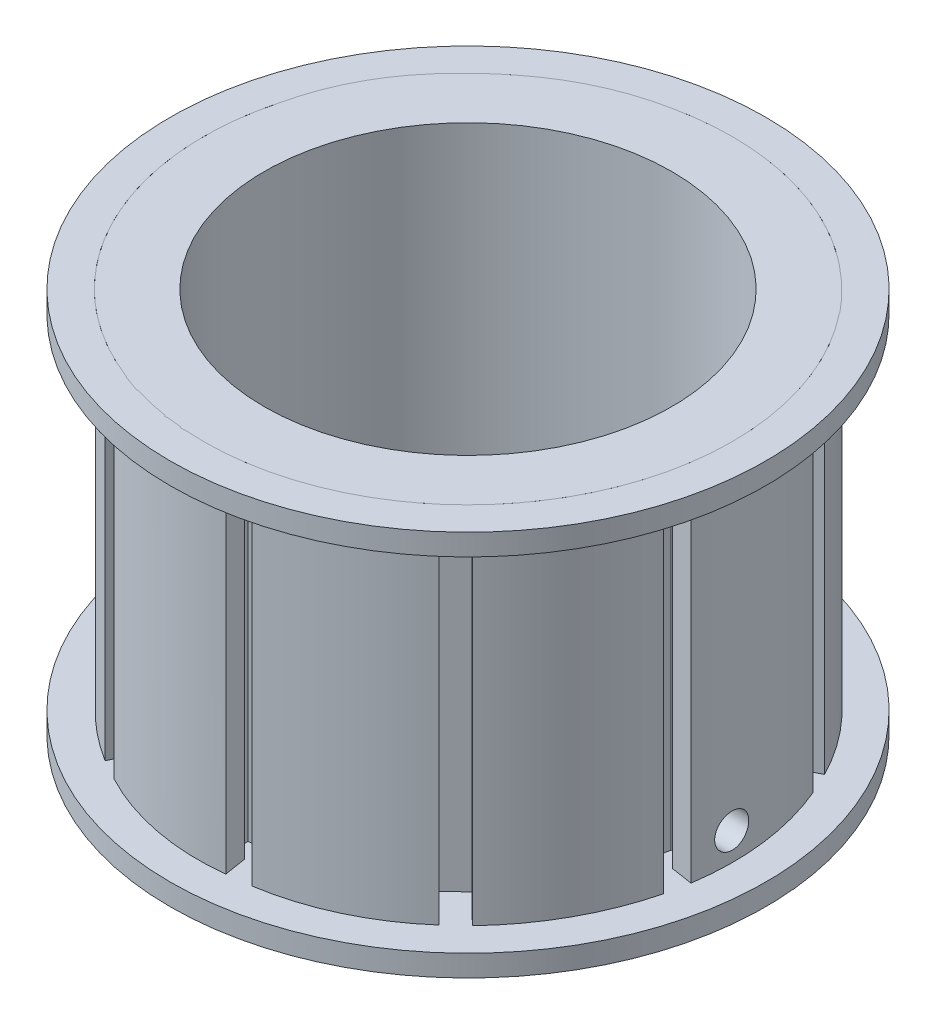
SolidWorks part; units mm, degrees
ref_plane "Alzado" through (0, 0, 0) normal (0, 0, 1) x (1, 0, 0)
ref_plane "Planta" through (0, 0, 0) normal (0, 1, 0) x (1, 0, 0)
ref_plane "Vista lateral" through (0, 0, 0) normal (1, 0, 0) x (0, 0, -1)
sketch "Sketch3" plane through (0, 0, 0) normal (1, 0, 0) x (0, 0, -1)
  line L0 (0, 0) -> (0, 36)
  dimension "D1" = 36
sketch "Sketch2" plane through (0, 0, 0) normal (0, 1, 0) x (1, 0, 0)
  circle A0 centre (0, 0) radius 24.5
sketch "Sketch1" plane through (0, 0, 0) normal (0, 1, 0) x (1, 0, 0)
  line L0 (0, 0) -> (-24.5, 0) construction
  line L1 (0, 0) -> (0, 24.5) construction
  line L2 (0, 0) -> (0, -24.5) construction
  line L3 (0, 0) -> (24.5, 0) construction
  line L4 (0, 0) -> (-24.179, 4.7253) construction
  line L5 (-17.5664, 3.433) -> (-17.9871, 1.2802) construction
  line L6 (-17.9871, 1.2802) -> (-20.8948, 1.8485) construction
  line L7 (-20.8948, 1.8485) -> (-20.6845, 2.9249) construction
  line L8 (-20.6845, 2.9249) -> (-24.2404, 3.557) construction
  line L9 (-17.9871, 1.2802) -> (-17.1533, 5.5802) construction
  line L10 (-20.0277, 6.1489) -> (-20.2564, 5.0738) construction
  line L11 (-20.0277, 6.1489) -> (-17.1459, 5.586) construction
  line L12 (-20.2564, 5.0738) -> (-23.8257, 5.7083) construction
  line L13 (-24.2404, 3.557) -> (-20.6845, 2.9249)
  line L14 (-20.6845, 2.9249) -> (-20.8948, 1.8485)
  line L15 (-20.8948, 1.8485) -> (-17.9871, 1.2802)
  line L16 (-17.9871, 1.2802) -> (-17.1533, 5.5802)
  line L17 (-17.1533, 5.5802) -> (-20.0277, 6.1489)
  line L18 (-20.0277, 6.1489) -> (-20.2564, 5.0738)
  line L19 (-20.2564, 5.0738) -> (-23.8257, 5.7083)
  line L20 (-20.2564, 5.0738) -> (-20.6845, 2.9249) construction
  circle A1 centre (0, 0) radius 24.5 construction
  arc A3 (-23.8257, 5.7083) -> (-24.2404, 3.557) centre (0, 0) cw
  dimension "D1" = 24.5
  dimension "D2" = 24.5
  dimension "D3" = 24.5
  dimension "D4" = 24.5
ref_plane "Plane4" through (0, 0, 0) normal (1, 0, 0) x (0, 0, -1)
sketch "Sketch5" plane through (0, 0, 0) normal (0, 1, 0) x (1, 0, 0)
  line L0 (0.0754, 0) -> (-24.4246, 0) construction
  line L1 (0.0754, 0) -> (0.0754, 24.5) construction
  line L2 (0.0754, 0) -> (0.0754, -24.5) construction
  line L3 (0.0754, 0) -> (24.5754, 0) construction
  line L4 (0.0754, 0) -> (-24.1036, 4.7253) construction
  line L5 (-17.5664, 3.433) -> (-20.7765, 1.8254) construction
  line L6 (-20.7765, 1.8254) -> (-22.5261, 2.1673) construction
  line L7 (-22.5261, 2.1673) -> (-22.3133, 3.2565) construction
  line L8 (-22.3133, 3.2565) -> (-24.363, 3.5724) construction
  line L9 (-20.7765, 1.8254) -> (-19.9414, 6.1319) construction
  line L10 (-21.677, 6.4753) -> (-21.8849, 5.4053) construction
  line L11 (-21.677, 6.4753) -> (-17.1459, 5.586) construction
  line L12 (-21.8849, 5.4053) -> (-23.9442, 5.7227) construction
  line L13 (-24.363, 3.5724) -> (-22.3133, 3.2565)
  line L14 (-22.3133, 3.2565) -> (-22.5261, 2.1673)
  line L15 (-22.5261, 2.1673) -> (-20.7765, 1.8254)
  line L16 (-20.7765, 1.8254) -> (-19.9414, 6.1319)
  line L17 (-19.9414, 6.1319) -> (-21.677, 6.4753)
  line L18 (-21.677, 6.4753) -> (-21.8849, 5.4053)
  line L19 (-21.8849, 5.4053) -> (-23.9442, 5.7227)
  line L20 (-21.8849, 5.4053) -> (-22.3133, 3.2565) construction
  line L21 (0, 0) -> (-24.5, 0) construction
  line L22 (-17.6103, 17.2103) -> (-16.1377, 15.7499)
  line L23 (-16.1377, 15.7499) -> (-16.9501, 14.9939)
  line L24 (-16.9501, 14.9939) -> (-15.7356, 13.6889)
  line L25 (-15.7356, 13.6889) -> (-12.5287, 16.6821)
  line L26 (-12.5287, 16.6821) -> (-13.731, 17.98)
  line L27 (-13.731, 17.98) -> (-14.5281, 17.2367)
  line L28 (-14.5281, 17.2367) -> (-16.0075, 18.7038)
  line L29 (-4.1311, 24.2745) -> (-3.7981, 22.2275)
  line L30 (-3.7981, 22.2275) -> (-4.8997, 22.0934)
  line L31 (-4.8997, 22.0934) -> (-4.6843, 20.3237)
  line L32 (-4.6843, 20.3237) -> (-0.3305, 20.8603)
  line L33 (-0.3305, 20.8603) -> (-0.5402, 22.6171)
  line L34 (-0.5402, 22.6171) -> (-1.622, 22.4842)
  line L35 (-1.622, 22.4842) -> (-1.9565, 24.5407)
  line L36 (10.9261, 22.0667) -> (9.9923, 20.2149)
  line L37 (9.9923, 20.2149) -> (9.0222, 20.7539)
  line L38 (9.0222, 20.7539) -> (8.1563, 19.1955)
  line L39 (8.1563, 19.1955) -> (11.994, 17.0706)
  line L40 (11.994, 17.0706) -> (12.8569, 18.6151)
  line L41 (12.8569, 18.6151) -> (11.9036, 19.1435)
  line L42 (11.9036, 19.1435) -> (12.8418, 21.0039)
  line L43 (21.8098, 11.4301) -> (19.9659, 10.4809)
  line L44 (19.9659, 10.4809) -> (19.4979, 11.4872)
  line L45 (19.4979, 11.4872) -> (17.8814, 10.7354)
  line L46 (17.8814, 10.7354) -> (19.7372, 6.7605)
  line L47 (19.7372, 6.7605) -> (21.3432, 7.5028)
  line L48 (21.3432, 7.5028) -> (20.8825, 8.4906)
  line L49 (20.8825, 8.4906) -> (22.735, 9.4443)
  line L50 (24.363, -3.5724) -> (22.3133, -3.2565)
  line L51 (22.3133, -3.2565) -> (22.5261, -2.1673)
  line L52 (22.5261, -2.1673) -> (20.7765, -1.8254)
  line L53 (20.7765, -1.8254) -> (19.9414, -6.1319)
  line L54 (19.9414, -6.1319) -> (21.677, -6.4753)
  line L55 (21.677, -6.4753) -> (21.8849, -5.4053)
  line L56 (21.8849, -5.4053) -> (23.9442, -5.7227)
  line L57 (17.6103, -17.2103) -> (16.1377, -15.7499)
  line L58 (16.1377, -15.7499) -> (16.9501, -14.9939)
  line L59 (16.9501, -14.9939) -> (15.7356, -13.6889)
  line L60 (15.7356, -13.6889) -> (12.5287, -16.6821)
  line L61 (12.5287, -16.6821) -> (13.731, -17.98)
  line L62 (13.731, -17.98) -> (14.5281, -17.2367)
  line L63 (14.5281, -17.2367) -> (16.0075, -18.7038)
  line L64 (4.1311, -24.2745) -> (3.7981, -22.2275)
  line L65 (3.7981, -22.2275) -> (4.8997, -22.0934)
  line L66 (4.8997, -22.0934) -> (4.6843, -20.3237)
  line L67 (4.6843, -20.3237) -> (0.3305, -20.8603)
  line L68 (0.3305, -20.8603) -> (0.5402, -22.6171)
  line L69 (0.5402, -22.6171) -> (1.622, -22.4842)
  line L70 (1.622, -22.4842) -> (1.9565, -24.5407)
  line L71 (-10.9261, -22.0667) -> (-9.9923, -20.2149)
  line L72 (-9.9923, -20.2149) -> (-9.0222, -20.7539)
  line L73 (-9.0222, -20.7539) -> (-8.1563, -19.1955)
  line L74 (-8.1563, -19.1955) -> (-11.994, -17.0706)
  line L75 (-11.994, -17.0706) -> (-12.8569, -18.6151)
  line L76 (-12.8569, -18.6151) -> (-11.9036, -19.1435)
  line L77 (-11.9036, -19.1435) -> (-12.8418, -21.0039)
  line L78 (-21.8098, -11.4301) -> (-19.9659, -10.4809)
  line L79 (-19.9659, -10.4809) -> (-19.4979, -11.4872)
  line L80 (-19.4979, -11.4872) -> (-17.8814, -10.7354)
  line L81 (-17.8814, -10.7354) -> (-19.7372, -6.7605)
  line L82 (-19.7372, -6.7605) -> (-21.3432, -7.5028)
  line L83 (-21.3432, -7.5028) -> (-20.8825, -8.4906)
  line L84 (-20.8825, -8.4906) -> (-22.735, -9.4443)
  arc A12 (-24.363, 3.5724) -> (-22.735, -9.4443) centre (-0.5159, -0.0552) ccw
  arc A13 (-21.8098, -11.4301) -> (-12.8418, -21.0039) centre (0.6864, 0.6556) ccw
  arc A14 (-10.9261, -22.0667) -> (1.9565, -24.5407) centre (-0.4657, -2.3758) ccw
  arc A15 (4.1311, -24.2745) -> (16.0075, -18.7038) centre (0.5253, -1.1418) ccw
  arc A19 (12.8418, 21.0039) -> (21.8098, 11.4301) centre (0.8003, 0.737) cw
  arc A20 (22.735, 9.4443) -> (24.363, -3.5724) centre (0.6279, 0.0692) cw
  arc A23 (17.6103, -17.2103) -> (23.9442, -5.7227) centre (-0.9852, 0.5326) ccw
  arc A24 (-1.9565, 24.5407) -> (10.9261, 22.0667) centre (-0.0263, -0.1859) cw
  arc A25 (-23.9442, 5.7227) -> (-17.6103, 17.2103) centre (-3.0155, 1.6732) cw
  arc A26 (-16.0075, 18.7038) -> (-4.1311, 24.2745) centre (-0.6941, 1.5015) cw
  point P96 (0, 0)
  dimension "D1" = 10
extrude "Boss-Extrude1" add sketch "Sketch5" along normal blind 36
sketch "Sketch7" plane through (0, 36, 0) normal (0, 1, 0) x (1, 0, 0)
  circle A1 centre (0, 0) radius 19
  dimension "D1" = 38
extrude "Cut-Extrude2" cut sketch "Sketch7" against normal blind 28
sketch "Sketch8" plane through (0, 36, 0) normal (0, 1, 0) x (1, 0, 0)
  circle A0 centre (0, 0) radius 24.6403
  circle A1 centre (0, 0) radius 19
  dimension "D1" = 38
extrude "Boss-Extrude2" add sketch "Sketch8" against normal blind 2
sketch "Sketch9" plane through (0, 0, 0) normal (0, -1, 0) x (1, 0, 0)
  circle A0 centre (0, 0) radius 24.7655
  circle A1 centre (0, 0) radius 19
  dimension "D1" = 38
extrude "Boss-Extrude3" add sketch "Sketch9" against normal blind 2
ref_plane "Plane6" through (100, 0, 0) normal (1, 0, 0) x (0, 0, -1)
sketch "Sketch12" plane through (100, 0, 0) normal (1, 0, 0) x (0, 0, -1)
  line L0 (-24.7655, 0) -> (24.7655, 0) construction
  circle A0 centre (0, 4.5985) radius 1.585
  dimension "D1" = 3.17
  dimension "D2" = 4.5985
extrude "Cut-Extrude4" cut sketch "Sketch12" against normal through all and the other way through all
ref_plane "Plane9" through (0, 0, 0) normal (0, 0, 1) x (1, 0, 0)
ref_plane "Plane10" through (0, 0, 0) normal (1, 0, 0) x (0, 0, -1)
ref_plane "Plane11" through (0, 0, 0) normal (0.7071, 0, -0.7071) x (-0.7071, 0, -0.7071)
sketch "Sketch16" plane through (0, 0, 0) normal (0.7071, 0, -0.7071) x (-0.7071, 0, -0.7071)
  line L0 (-24.7655, 0) -> (24.7655, 0) construction
  circle A0 centre (0.6135, 4.5985) radius 1.585
  dimension "D1" = 3.17
  dimension "D2" = 4.5985
sketch "Sketch17" plane through (0, 0, 0) normal (0, -1, 0) x (1, 0, 0)
  circle A0 centre (0, 0) radius 27.7655
  circle A1 centre (0, 0) radius 24.7655 construction
  point P4 (0, 0)
  dimension "D1" = 3
extrude "Boss-Extrude4" add sketch "Sketch17" against normal blind 2
sketch "Sketch18" plane through (0, 36, 0) normal (0, 1, 0) x (1, 0, 0)
  circle A0 centre (0, 0) radius 27.7655
  circle A2 centre (0, 0) radius 24.6403
extrude "Boss-Extrude5" add sketch "Sketch18" against normal blind 2 separate body
sketch "Sketch6" plane through (0, 36, 0) normal (0, 1, 0) x (1, 0, 0)
  circle A1 centre (0, 0) radius 4
  dimension "D1" = 8
extrude "Cut-Extrude1" cut sketch "Sketch6" against normal through all
